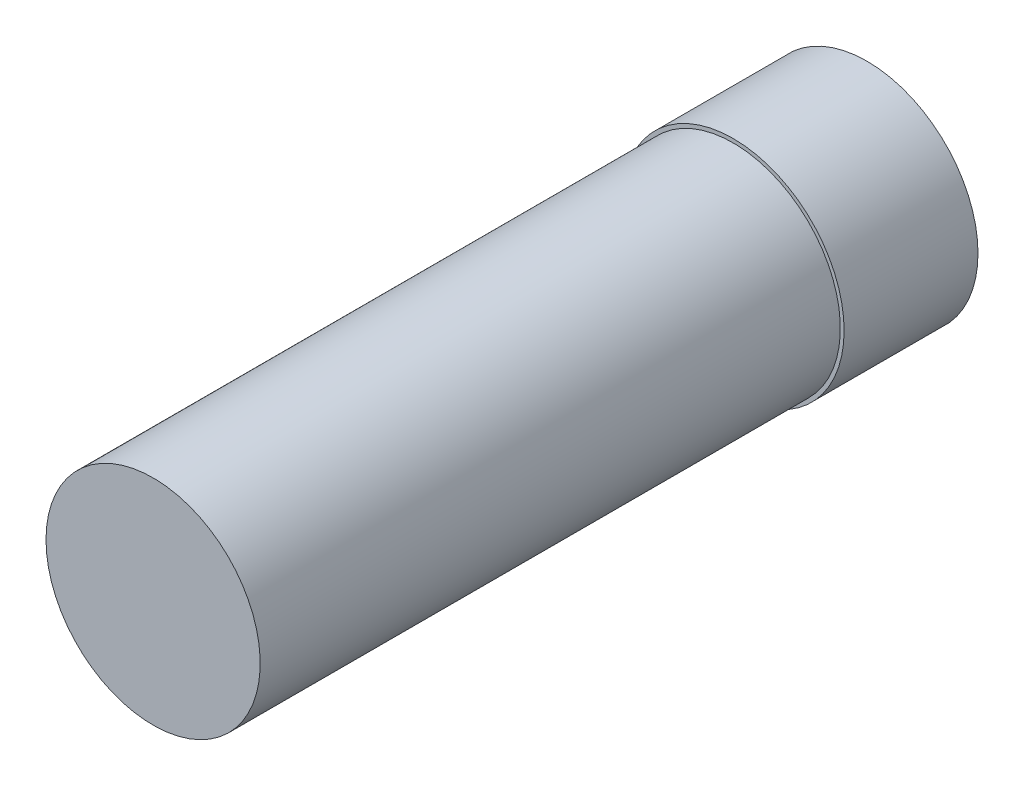
SolidWorks part; units mm, degrees
ref_plane "정면" through (0, 0, 0) normal (0, 0, 1) x (1, 0, 0)
ref_plane "윗면" through (0, 0, 0) normal (0, 1, 0) x (1, 0, 0)
ref_plane "우측면" through (0, 0, 0) normal (1, 0, 0) x (0, 0, -1)
sketch "스케치1" plane through (0, 0, 0) normal (0, 0, 1) x (1, 0, 0)
  circle A0 centre (0, 0) radius 2.485
  dimension "D1" = 4.97
extrude "보스-돌출1" add sketch "스케치1" along normal blind 3
sketch "스케치2" plane through (0, 0, 3) normal (0, 0, 1) x (1, 0, 0)
  circle A0 centre (0, 0) radius 2.4
  dimension "D1" = 4.8
extrude "보스-돌출2" add sketch "스케치2" along normal blind 13
sketch "스케치3" plane through (0, 0, 16) normal (0, 0, 1) x (1, 0, 0)
  circle A0 centre (0, 0) radius 2.45
  dimension "D1" = 4.9
